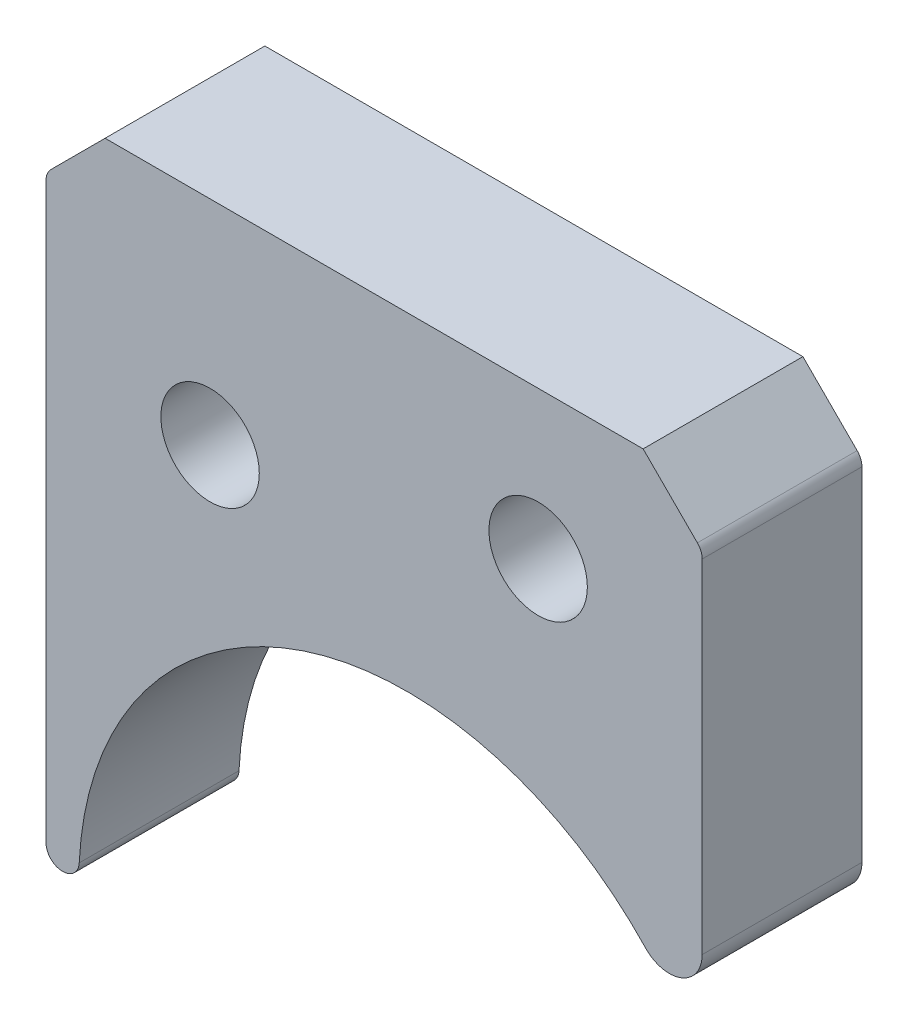
SolidWorks part; units mm, degrees
ref_plane "Front Plane" through (0, 0, 0) normal (0, 0, 1) x (1, 0, 0)
ref_plane "Top Plane" through (0, 0, 0) normal (0, 1, 0) x (1, 0, 0)
ref_plane "Right Plane" through (0, 0, 0) normal (1, 0, 0) x (0, 0, -1)
sketch "Sketch1" plane through (0, 0, 0) normal (0, 0, 1) x (1, 0, 0)
  line L1 (0, 0) -> (1, 0)
  line L2 (0, 0) -> (0, 20)
  line L3 (0, 20) -> (20, 20)
  line L4 (20, 4.3589) -> (20, 20)
  arc A0 (20, 4.3589) -> (1, 0) centre (11, 0) ccw
extrude "Boss-Extrude1" add sketch "Sketch1" along normal blind 4.87
sketch "Sketch2" plane through (0, 0, 4.87) normal (0, 0, 1) x (1, 0, 0)
  line L0 (5, 15.5) -> (11, 15.5) construction
  line L1 (11, 15.5) -> (15, 15.5) construction
  line L2 (11, 15.5) -> (11, 0) construction
  line L3 (5, 15.5) -> (5, 13.5) construction
  circle A0 centre (5, 13.5) radius 1.5
  circle A1 centre (15, 15.5) radius 1.5
  dimension "D5" = 15.5
  dimension "D4" = 3
  dimension "D1" = 11
  dimension "D2" = 6
  dimension "D3" = 2
  dimension "D6" = 4
extrude "Cut-Extrude1" cut sketch "Sketch2" against normal blind 4.87
chamfer "Chamfer1" distance 1.8 angle 45 2 edges at (0, 20, 2.435) (20, 20, 2.435)
fillet "Fillet1" radius 0.5 4 edges at (0, 0, 2.435) (1, 0, 2.435) (20, 18.2, 2.435) (0, 18.2, 2.435)
fillet "Fillet2" radius 1 1 edges at (20, 4.3589, 2.435)
